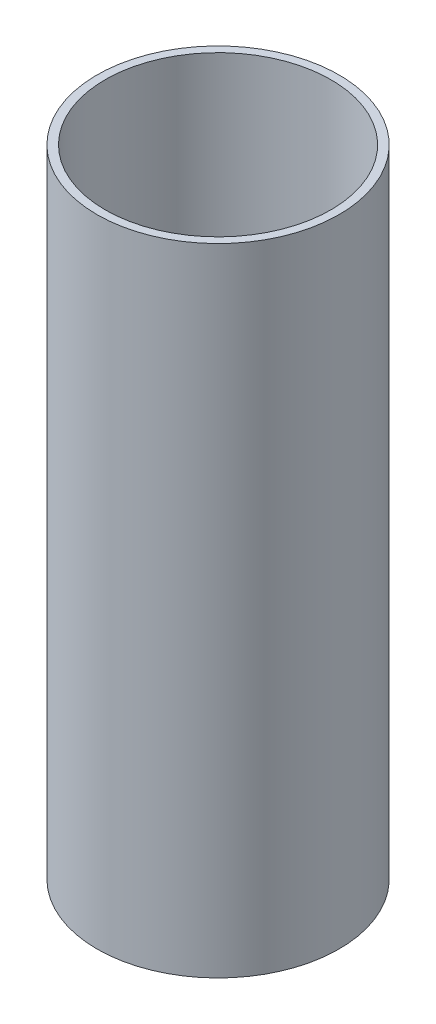
SolidWorks part; units mm, degrees
ref_plane "Front Plane" through (0, 0, 0) normal (0, 0, 1) x (1, 0, 0)
ref_plane "Top Plane" through (0, 0, 0) normal (0, 1, 0) x (1, 0, 0)
ref_plane "Right Plane" through (0, 0, 0) normal (1, 0, 0) x (0, 0, -1)
sketch "Sketch1" plane through (0, 0, 0) normal (0, 1, 0) x (1, 0, 0)
  circle A0 centre (0, 0) radius 37.7
  circle A1 centre (0, 0) radius 35.15
  dimension "D1" = 75.4
  dimension "D2" = 70.3
extrude "Boss-Extrude1" add sketch "Sketch1" along normal blind 198.12
